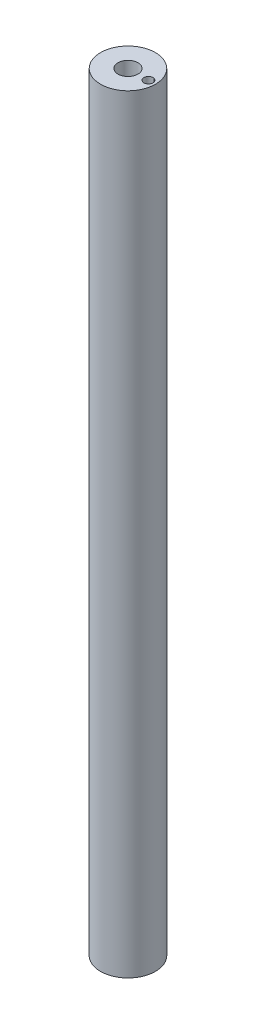
SolidWorks part; units mm, degrees
ref_plane "Front Plane" through (0, 0, 0) normal (0, 0, 1) x (1, 0, 0)
ref_plane "Top Plane" through (0, 0, 0) normal (0, 1, 0) x (1, 0, 0)
ref_plane "Right Plane" through (0, 0, 0) normal (1, 0, 0) x (0, 0, -1)
sketch "Sketch1" plane through (0, 0, 0) normal (0, 1, 0) x (1, 0, 0)
  circle A0 centre (0, 0) radius 4.7625
  dimension "D1" = 9.525
extrude "Boss-Extrude1" add sketch "Sketch1" along normal blind 133.35
hole_wizard "#8-32 Tapped Hole1" positions "3DSketch1" profile "Sketch2" tap size "#8-32" standard "ANSI Inch"
sketch3d "3DSketch1"
  line L0 (0, 133.35, 0) -> (0, 0, 0) construction
  point P0 (0, 133.35, 0)
  point P27 (0, 0, 0)
sketch "Sketch2" plane through (0, 133.35, 0) normal (1, 0, 0) x (0, 0, 1)
  line L0 (0, 0) -> (0, 11.7058)
  line L1 (0, 11.7058) -> (1.7272, 10.668)
  line L2 (1.7272, 10.668) -> (1.7272, 0)
  line L5 (1.7272, 0) -> (0, 0)
  line L10 (0, 11.7058) -> (-1.7272, 10.668) construction
  line L11 (0, -6.35) -> (0, 107.95) construction
  dimension "Tap Drill Dia." = 3.4544
  dimension "Tap Drill Depth" = 10.668
  dimension "Drill Angle" = 118
cosmetic thread "Hole Thread9" parameters "D1"=8.382, "D2"=4.1656
cosmetic thread "Hole Thread10" parameters "D1"=8.382, "D2"=4.1656
hole_wizard "1/16 (0.0625) Diameter Hole1" positions "3DSketch3" profile "Sketch6" hole size "1/16" standard "ANSI Inch"
sketch3d "3DSketch3"
  circle A0 centre (0, 133.35, 0) radius 1.7272 construction
  circle A1 centre (0, 133.35, 0) radius 1.7272 construction
  point P0 (3.556, 0, 0)
  point P7 (3.556, 133.35, 0)
  point P10 (3.3156, 133.35, 0.0612)
  point P11 (0, 0, 0)
  point P13 (0, 0, 0)
  point P14 (0, 0, 0)
  point P17 (0, 135.0772, 0)
  point P19 (0, 135.0772, 0)
  point P20 (0, 0, 0)
  dimension "D1" = 3.556
  dimension "D2" = 3.556
sketch "Sketch6" plane through (3.556, 0, 0) normal (1, 0, 0) x (0, 0, -1)
  line L0 (0, 0) -> (0, 5.2394)
  line L1 (0, 5.2394) -> (0.7937, 4.7625)
  line L2 (0.7937, 4.7625) -> (0.7937, 0)
  line L5 (0.7937, 0) -> (0, 0)
  line L10 (0, 5.2394) -> (-0.7938, 4.7625) construction
  line L11 (0, -6.35) -> (0, 107.95) construction
  dimension "Hole Dia." = 1.5875
  dimension "Hole Depth" = 4.7625
  dimension "Drill Angle" = 118
